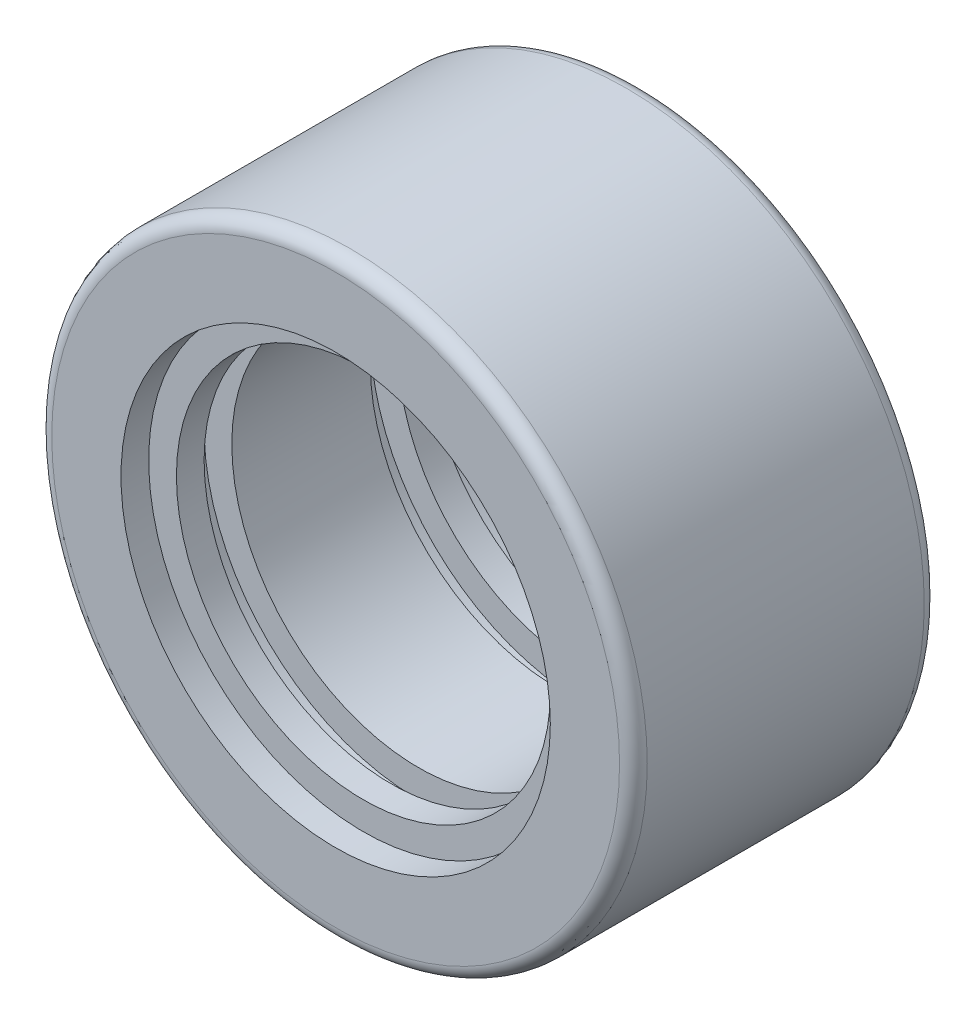
SolidWorks part; units mm, degrees
material "Силиконовая резина"
ref_plane "Спереди" through (0, 0, 0) normal (0, 0, 1) x (1, 0, 0)
ref_plane "Сверху" through (0, 0, 0) normal (0, 1, 0) x (1, 0, 0)
ref_plane "Справа" through (0, 0, 0) normal (1, 0, 0) x (0, 0, -1)
sketch "Эскиз1" plane through (0, 0, 0) normal (1, 0, 0) x (0, 0, -1)
  line L0 (0, 22.1566) -> (0, -19.2187) construction
  line L1 (-10, 21.5) -> (10, 21.5)
  line L2 (11, 20.5) -> (11, 15.5)
  line L3 (11, 15.5) -> (9, 15.5)
  line L4 (9, 15.5) -> (9, 13.5)
  line L5 (9, 13.5) -> (7, 13.5)
  line L6 (7, 13.5) -> (7, 15.5)
  line L7 (7, 15.5) -> (5, 15.5)
  line L8 (5, 15.5) -> (5, 13.5)
  line L9 (5, 13.5) -> (-5, 13.5)
  line L10 (0, 13.5) -> (0, 21.5)
  line L11 (-20.3904, 0) -> (21.297, 0) construction
  line L12 (-5, 15.5) -> (-5, 13.5)
  line L13 (-7, 15.5) -> (-5, 15.5)
  line L14 (-7, 13.5) -> (-7, 15.5)
  line L15 (-9, 13.5) -> (-7, 13.5)
  line L16 (-9, 15.5) -> (-9, 13.5)
  line L17 (-11, 15.5) -> (-9, 15.5)
  line L18 (-11, 20.5) -> (-11, 15.5)
  arc A0 (-11, 20.5) -> (-10, 21.5) centre (-10, 20.5) cw
  arc A1 (10, 21.5) -> (11, 20.5) centre (10, 20.5) cw
  point P25 (-11, 21.5)
  point P28 (11, 21.5)
  dimension "D7" = 1
  dimension "D1" = 22
  dimension "D2" = 2
  dimension "D3" = 2
  dimension "D4" = 2
  dimension "D5" = 2
  dimension "D6" = 8
  dimension "7" = 27
revolve "Повернуть1" add sketch "Эскиз1" angle 360 about L11
